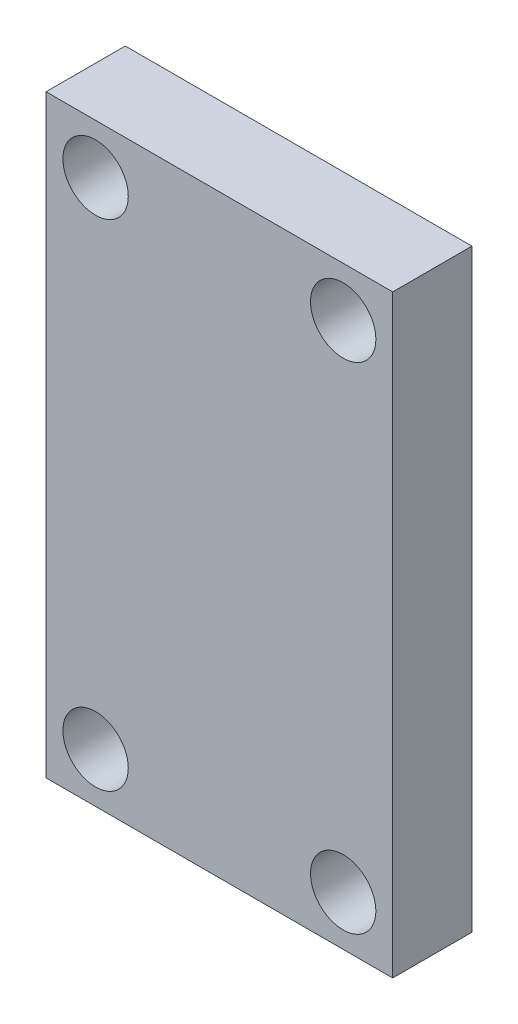
SolidWorks part; units mm, degrees
ref_plane "Front Plane" through (0, 0, 0) normal (0, 0, 1) x (1, 0, 0)
ref_plane "Top Plane" through (0, 0, 0) normal (0, 1, 0) x (1, 0, 0)
ref_plane "Right Plane" through (0, 0, 0) normal (1, 0, 0) x (0, 0, -1)
sketch "Sketch1" plane through (0, 0, 0) normal (0, 0, 1) x (1, 0, 0)
  line L1 (-17.5, 30) -> (17.5, 30)
  line L2 (-17.5, 30) -> (-17.5, -30)
  line L3 (-17.5, -30) -> (17.5, -30)
  line L4 (17.5, 30) -> (17.5, -30)
  line L5 (0, -30) -> (0, 30) construction
  line L6 (-17.5, 0) -> (17.5, 0) construction
  point P0 (0, 0)
  dimension "D1" = 60
  dimension "D2" = 35
extrude "Boss-Extrude1" add sketch "Sketch1" along normal mid plane 8
hole_wizard "M6 Clearance Hole1" positions "Sketch2" profile "Sketch3" hole size "M6" standard "ISO"
sketch "Sketch2" plane through (0, 0, 4) normal (0, 0, 1) x (1, 0, 0)
  line L0 (-17.5, 30) -> (-17.5, -30) construction
  line L1 (-17.5, 30) -> (17.5, 30) construction
  point P0 (-12.5, 25)
  dimension "D1" = 5
  dimension "D2" = 5
sketch "Sketch3" plane through (-12.5, 25, 4) normal (1, 0, 0) x (0, -1, 0)
  line L0 (0, 0) -> (0, 9.9828)
  line L1 (0, 9.9828) -> (3.3, 8)
  line L2 (3.3, 8) -> (3.3, 0)
  line L5 (3.3, 0) -> (0, 0)
  line L10 (0, 9.9828) -> (-3.3, 8) construction
  line L11 (0, -6.35) -> (0, 107.95) construction
  dimension "Hole Dia." = 6.6
  dimension "Hole Depth" = 8
  dimension "Drill Angle" = 118
mirror "Mirror1" about plane through (0, 0, 0) normal (1, 0, 0) of "M6 Clearance Hole1"
mirror "Mirror2" about plane through (0, 0, 0) normal (0, 1, 0) of "Mirror1", "M6 Clearance Hole1"
